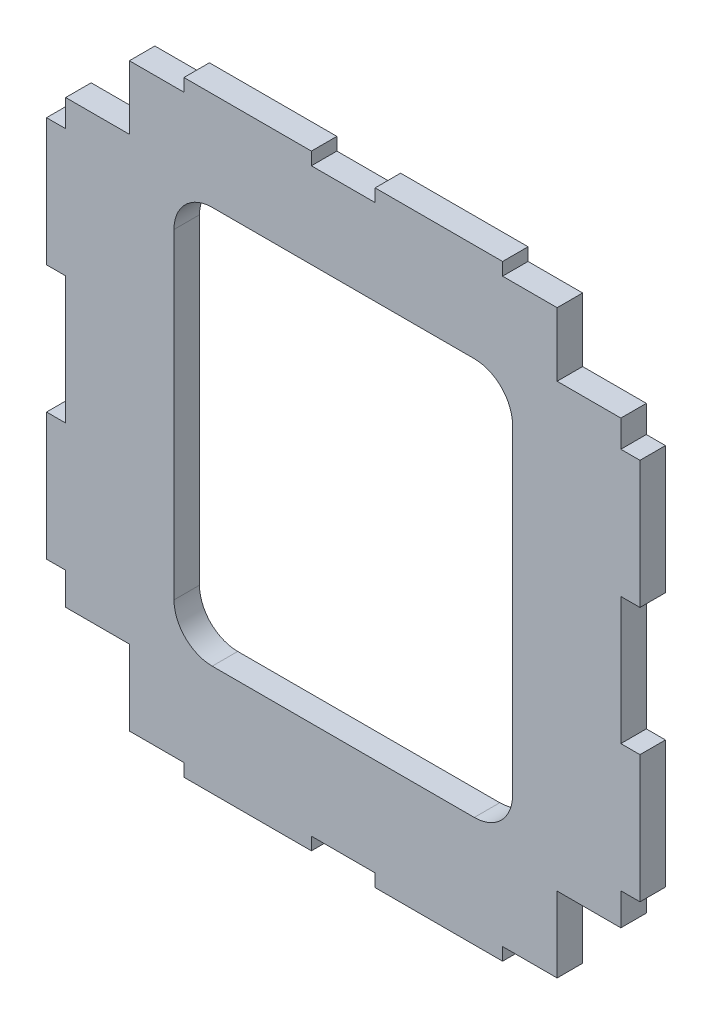
SolidWorks part; units mm, degrees
ref_plane "前视基准面" through (0, 0, 0) normal (0, 0, 1) x (1, 0, 0)
ref_plane "上视基准面" through (0, 0, 0) normal (0, 1, 0) x (1, 0, 0)
ref_plane "右视基准面" through (0, 0, 0) normal (1, 0, 0) x (0, 0, -1)
sketch "Model" plane through (0, 0, 0) normal (0, 0, 1) x (1, 0, 0)
  line L0 (57.0547, 46.3462) -> (36.4947, 46.3462)
  line L1 (60.0547, 43.3462) -> (60.0547, 18.1762)
  line L2 (36.4947, 15.1762) -> (57.0547, 15.1762)
  line L3 (33.4947, 43.3462) -> (33.4947, 18.1762)
  line L4 (29.9947, 53.0633) -> (34.2747, 53.0633)
  line L5 (34.2747, 53.0633) -> (34.2747, 54.0637)
  line L6 (34.2747, 54.0637) -> (44.2747, 54.0637)
  line L7 (44.2747, 54.0637) -> (44.2747, 53.0633)
  line L8 (44.2747, 53.0633) -> (49.2747, 53.0633)
  line L9 (49.2747, 53.0633) -> (49.2747, 54.0637)
  line L10 (49.2747, 54.0637) -> (59.2747, 54.0637)
  line L11 (59.2747, 54.0637) -> (59.2747, 53.0633)
  line L12 (59.2747, 53.0633) -> (63.5547, 53.0633)
  line L13 (29.9947, 7.5164) -> (34.2747, 7.5164)
  line L14 (34.2747, 7.5164) -> (34.2747, 6.5161)
  line L15 (34.2747, 6.5161) -> (44.2747, 6.5161)
  line L16 (44.2747, 6.5161) -> (44.2747, 7.5164)
  line L17 (44.2747, 7.5164) -> (49.2747, 7.5164)
  line L18 (49.2747, 7.5164) -> (49.2747, 6.5161)
  line L19 (49.2747, 6.5161) -> (59.2747, 6.5161)
  line L20 (59.2747, 6.5161) -> (59.2747, 7.5164)
  line L21 (59.2747, 7.5164) -> (63.5547, 7.5164)
  line L22 (23.4947, 15.9433) -> (23.4947, 25.9433)
  line L23 (23.4947, 35.9433) -> (23.4947, 45.9433)
  line L24 (24.9947, 48.0633) -> (29.9947, 48.0633)
  line L25 (29.9947, 48.0633) -> (29.9947, 53.0633)
  line L26 (24.9947, 13.4233) -> (29.9947, 13.4233)
  line L27 (29.9947, 13.4233) -> (29.9947, 7.5164)
  line L28 (24.9947, 48.0633) -> (24.9947, 45.9433)
  line L29 (24.9947, 45.9433) -> (23.4947, 45.9433)
  line L30 (23.4947, 35.9433) -> (24.9947, 35.9433)
  line L31 (24.9947, 35.9433) -> (24.9947, 25.9433)
  line L32 (24.9947, 25.9433) -> (23.4947, 25.9433)
  line L33 (23.4947, 15.9433) -> (24.9947, 15.9433)
  line L34 (24.9947, 15.9433) -> (24.9947, 13.4233)
  line L35 (70.0547, 15.9433) -> (70.0547, 25.9433)
  line L36 (70.0547, 35.9433) -> (70.0547, 45.9433)
  line L37 (68.5547, 48.0633) -> (63.5547, 48.0633)
  line L38 (63.5547, 48.0633) -> (63.5547, 53.0633)
  line L39 (68.5547, 13.4233) -> (63.5547, 13.4233)
  line L40 (63.5547, 13.4233) -> (63.5547, 7.5164)
  line L41 (68.5547, 48.0633) -> (68.5547, 45.9433)
  line L42 (68.5547, 45.9433) -> (70.0547, 45.9433)
  line L43 (70.0547, 35.9433) -> (68.5547, 35.9433)
  line L44 (68.5547, 35.9433) -> (68.5547, 25.9433)
  line L45 (68.5547, 25.9433) -> (70.0547, 25.9433)
  line L46 (70.0547, 15.9433) -> (68.5547, 15.9433)
  line L47 (68.5547, 15.9433) -> (68.5547, 13.4233)
  arc A0 (36.4947, 46.3462) -> (33.4947, 43.3462) centre (36.4947, 43.3462) ccw
  arc A1 (60.0547, 43.3462) -> (57.0547, 46.3462) centre (57.0547, 43.3462) ccw
  arc A2 (33.4947, 18.1762) -> (36.4947, 15.1762) centre (36.4947, 18.1762) ccw
  arc A3 (57.0547, 15.1762) -> (60.0547, 18.1762) centre (57.0547, 18.1762) ccw
extrude "凸台-拉伸1" add sketch "Model" along normal blind 2
